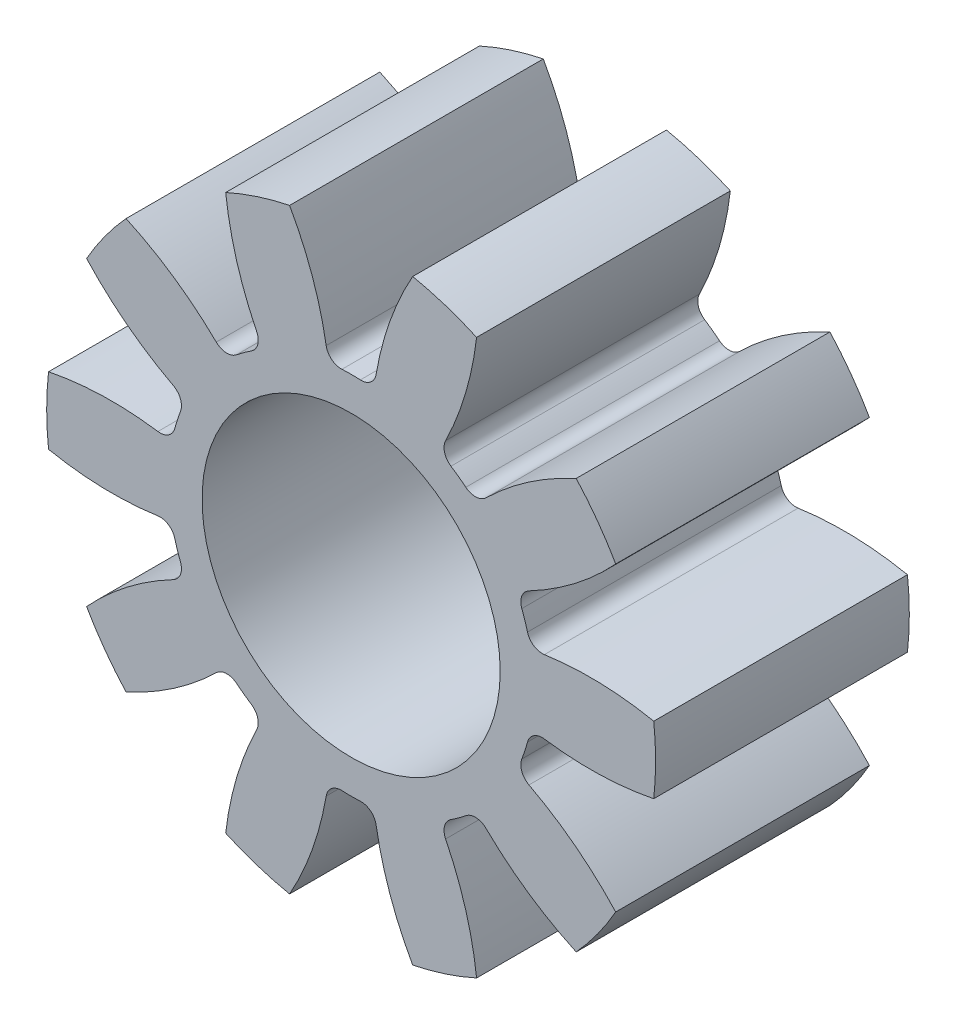
SolidWorks part; units mm, degrees
ref_plane "Front Plane" through (0, 0, 0) normal (0, 0, 1) x (1, 0, 0)
ref_plane "Top Plane" through (0, 0, 0) normal (0, 1, 0) x (1, 0, 0)
ref_plane "Right Plane" through (0, 0, 0) normal (1, 0, 0) x (0, 0, -1)
sketch "Sketch1" plane through (0, 0, 0) normal (0, 0, 1) x (1, 0, 0)
  circle A0 centre (0, 0) radius 4 construction
  circle A1 centre (0, 0) radius 4.8
  dimension "D1" = 8
  dimension "D2" = 9.6
extrude "Boss-Extrude1" add sketch "Sketch1" along normal mid plane 4 contours A1
sketch "Sketch13" plane through (0, 0, 0) normal (0, 0, 1) x (1, 0, 0)
  line L0 (0, 4.8) -> (0, 0) construction
  line L1 (0, 0) -> (2.8214, 3.8833) construction
  line L2 (0, 0) -> (1.4833, 4.5651) construction
  line L3 (-0.3612, 2.8573) -> (0, 0) construction
  line L4 (-0.6257, 3.9508) -> (0.6257, 3.9508) construction
  line L5 (0.6257, 3.9508) -> (1.816, 3.564) construction
  line L6 (-0.9036, 4.7142) -> (0, 2.2316) construction
  circle A0 centre (0, 0) radius 3.2 construction
  arc A1 (0.3612, 2.8573) -> (-0.3612, 2.8573) centre (0, 0) ccw
  circle A2 centre (0, 0) radius 4.8 construction
  arc A3 (-0.9706, 4.7008) -> (-0.3612, 2.8573) centre (-5.3693, 2.2242) cw
  circle A4 centre (0, 0) radius 4.8 construction
  arc A5 (0.9706, 4.7008) -> (0.3612, 2.8573) centre (5.3693, 2.2242) ccw
  circle A6 centre (0, 0) radius 4 construction
  arc A7 (0.9706, 4.7008) -> (-0.9706, 4.7008) centre (0, 0) ccw
  dimension "D1" = 36
  dimension "D2" = 1.6
  dimension "D3" = 1.92
  dimension "D4" = 20
extrude "Cut-Extrude9" cut sketch "Sketch13" against normal mid plane 4
fillet "Fillet1" radius 0.24 2 edges at (0.3612, 2.8573, 0) (-0.3612, 2.8573, 0)
pattern_circular "CirPattern1" count 10 over 360 about axis through (0, 0, 0) along (0, 0, 1) of "Cut-Extrude9", "Fillet1"
sketch "Sketch12" plane through (0, 0, 0) normal (0, 0, 1) x (1, 0, 0)
  circle A0 centre (0, 0) radius 2.35
  dimension "D1" = 4.7
extrude "Cut-Extrude8" cut sketch "Sketch12" against normal mid plane 10
equation "\"module\"= 0.8mm"
equation "\"number of teeth\"= 10"
equation "\"pressure angle\"= 20"
equation "\"D1@Sketch1\"=\"module\" * \"number of teeth\""
equation "\"D2@Sketch1\"= ( \"number of teeth\" + 2 ) * \"module\""
equation "\"D1@Sketch13\"=360 / \"number of teeth\""
equation "\"D2@Sketch13\"= \"module\" * 2"
equation "\"D3@Sketch13\"=\"module\" * if( \"module\" => 1.25, 2.25, 2.4 )"
equation "\"D4@Sketch13\"=\"pressure angle\""
equation "\"D1@Fillet1\"=0.3 * \"module\""
equation "\"D1@CirPattern1\"=\"number of teeth\""
equation "\"D2@Sketch7\"= \"module\" * 2"
equation "\"D4@Sketch7\"= \"module\" * 2.4"
equation "\"D2@Sketch6\"= ( \"teeth\" + 2 ) * \"module\""
equation "\"D1@Sketch6\"= \"module\" * \"teeth\""
equation "\"D3@Sketch2\"= \"module\" * 2"
equation "\"D2@Sketch2\"= 360 / \"number of teeth\""
equation "\"teeth\"= 7"
